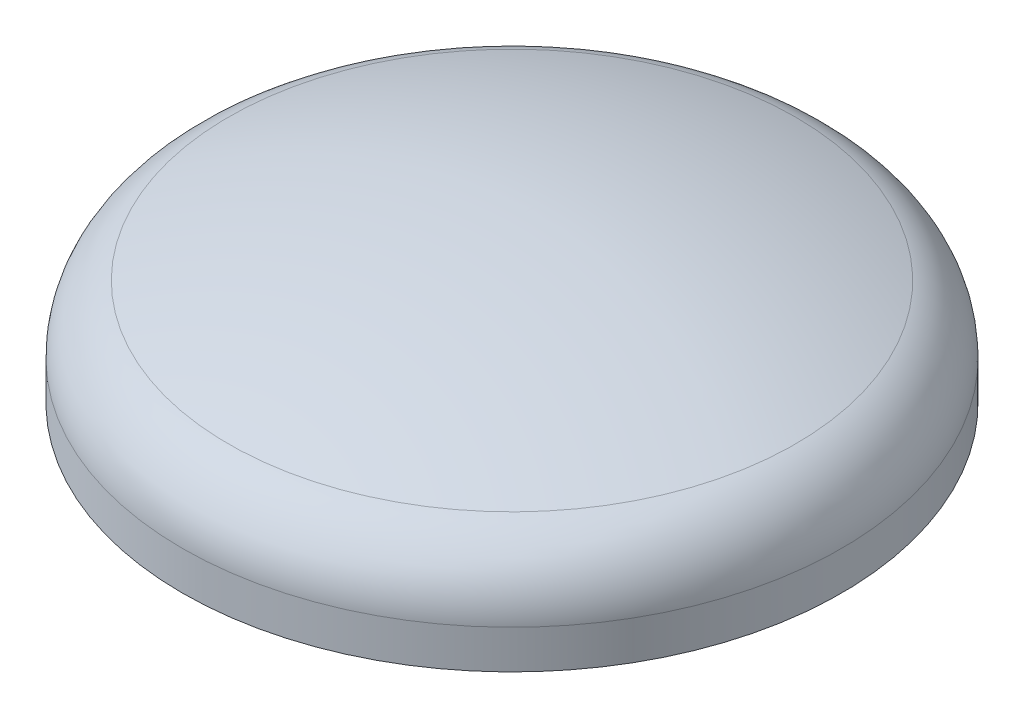
SolidWorks part; units mm, degrees
material "ASTM A36 Acero"
ref_plane "Alzado" through (0, 0, 0) normal (0, 0, 1) x (1, 0, 0)
ref_plane "Planta" through (0, 0, 0) normal (0, 1, 0) x (1, 0, 0)
ref_plane "Vista lateral" through (0, 0, 0) normal (1, 0, 0) x (0, 0, -1)
sketch "Croquis1" plane through (0, 0, 0) normal (0, 0, 1) x (1, 0, 0)
  line L0 (0, 0) -> (-228.6, 0)
  line L1 (0, 0) -> (0, 110)
  line L2 (-228.6, 0) -> (-228.6, 26.8421)
  arc A0 (-196.5469, 73.5102) -> (0, 110) centre (0.0001, -437.58) cw
  arc A1 (-228.6, 26.8421) -> (-196.5469, 73.5102) centre (-178.6, 26.8421) cw
  point P8 (-228.6, 60)
  dimension "D4" = 547.58
  dimension "D5" = 50
  dimension "D1" = 228.6
  dimension "D2" = 110
  dimension "D3" = 60
  dimension "D6" = 26.8421
revolve "Revolución1" add sketch "Croquis1" angle 360 about L1
shell "Vaciado1" thickness 9.525
